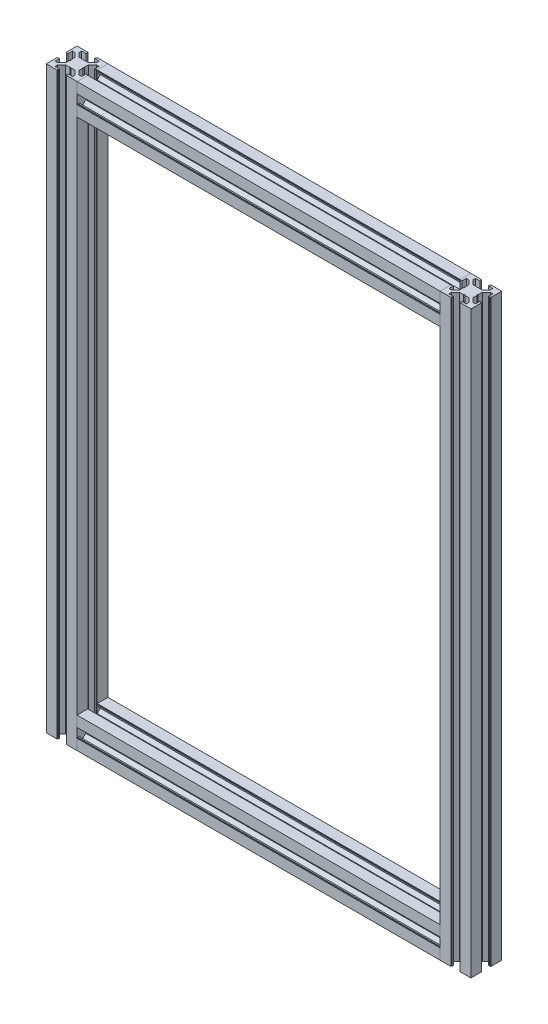
SolidWorks part; units mm, degrees
ref_plane "Ön Düzlem" through (0, 0, 0) normal (0, 0, 1) x (1, 0, 0)
ref_plane "Üst Düzlem" through (0, 0, 0) normal (0, 1, 0) x (1, 0, 0)
ref_plane "Sağ Düzlem" through (0, 0, 0) normal (1, 0, 0) x (0, 0, -1)
sketch "Sketch1" plane through (0, 0, 0) normal (0, 0, 1) x (1, 0, 0)
  line L1 (-192, 267.5) -> (192, 267.5)
  line L2 (-192, 267.5) -> (-192, -267.5)
  line L3 (-192, -267.5) -> (192, -267.5)
  line L4 (192, 267.5) -> (192, -267.5)
  line L5 (-192, 267.5) -> (192, -267.5) construction
  line L6 (-192, -267.5) -> (192, 267.5) construction
  point P0 (0, 0)
  dimension "D1" = 535
  dimension "D2" = 384
other "Square tube 30X30(1)"
ref_plane "Plane1" through (-192, 267.5, 0) normal (1, 0, 0) x (0, 1, 0)
sketch "Sketch11" plane through (-192, 267.5, 0) normal (1, 0, 0) x (0, 1, 0)
  line L0 (-14.9945, -4.5956) -> (-14.9945, -15.0055)
  line L1 (-14.9945, -15.0055) -> (-4.5847, -15.0055)
  line L2 (-4.5847, -15.0055) -> (-4.5847, -14.2046)
  line L3 (-4.5847, -14.2046) -> (-4.0945, -14.2046)
  line L4 (-4.0945, -14.2046) -> (-4.0945, -13.0055)
  line L5 (-4.0945, -13.0055) -> (-8.4945, -13.0055)
  line L6 (-8.4945, -13.0055) -> (-8.4945, -10.5542)
  line L7 (-8.4945, -10.5542) -> (-4.5847, -6.5055)
  line L8 (-4.5847, -6.5055) -> (-0.5548, -6.5055)
  line L9 (-0.5548, -6.5055) -> (0.0109, -5.9398)
  line L10 (0.0109, -5.9398) -> (0.5766, -6.5055)
  line L11 (0.5766, -6.5055) -> (4.5956, -6.5055)
  line L12 (4.5956, -6.5055) -> (8.5055, -10.5542)
  line L13 (8.5055, -10.5542) -> (8.5055, -13.0055)
  line L14 (8.5055, -13.0055) -> (4.1055, -13.0055)
  line L15 (4.1055, -13.0055) -> (4.1055, -14.2046)
  line L16 (4.1055, -14.2046) -> (4.5956, -14.2046)
  line L17 (4.5956, -14.2046) -> (4.5956, -15.0055)
  line L18 (4.5956, -15.0055) -> (15.0055, -15.0055)
  line L19 (15.0055, -15.0055) -> (15.0055, -4.5956)
  line L20 (15.0055, -4.5956) -> (14.2046, -4.5956)
  line L21 (14.2046, -4.5956) -> (14.2046, -4.1055)
  line L22 (14.2046, -4.1055) -> (13.0055, -4.1055)
  line L23 (13.0055, -4.1055) -> (13.0055, -8.5055)
  line L24 (13.0055, -8.5055) -> (10.5542, -8.5055)
  line L25 (10.5542, -8.5055) -> (6.5055, -4.5956)
  line L26 (6.5055, -4.5956) -> (6.5055, -0.5657)
  line L27 (6.5055, -0.5657) -> (5.9398, 0)
  line L28 (5.9398, 0) -> (6.5055, 0.5657)
  line L29 (6.5055, 0.5657) -> (6.5055, 4.5847)
  line L30 (6.5055, 4.5847) -> (10.5542, 8.4945)
  line L31 (10.5542, 8.4945) -> (13.0055, 8.4945)
  line L32 (13.0055, 8.4945) -> (13.0055, 4.0945)
  line L33 (13.0055, 4.0945) -> (14.2046, 4.0945)
  line L34 (14.2046, 4.0945) -> (14.2046, 4.5847)
  line L35 (14.2046, 4.5847) -> (15.0055, 4.5847)
  line L36 (15.0055, 4.5847) -> (15.0055, 14.9945)
  line L37 (15.0055, 14.9945) -> (4.5956, 14.9945)
  line L38 (4.5956, 14.9945) -> (4.5956, 14.1937)
  line L39 (4.5956, 14.1937) -> (4.1055, 14.1937)
  line L40 (4.1055, 14.1937) -> (4.1055, 12.9945)
  line L41 (4.1055, 12.9945) -> (8.5055, 12.9945)
  line L42 (8.5055, 12.9945) -> (8.5055, 10.5433)
  line L43 (8.5055, 10.5433) -> (4.5956, 6.4945)
  line L44 (4.5956, 6.4945) -> (0.5657, 6.4945)
  line L45 (0.5657, 6.4945) -> (0, 5.9289)
  line L46 (0, 5.9289) -> (-0.5657, 6.4945)
  line L47 (-0.5657, 6.4945) -> (-4.5847, 6.4945)
  line L48 (-4.5847, 6.4945) -> (-8.4945, 10.5433)
  line L49 (-8.4945, 10.5433) -> (-8.4945, 12.9945)
  line L50 (-8.4945, 12.9945) -> (-4.0945, 12.9945)
  line L51 (-4.0945, 12.9945) -> (-4.0945, 14.1937)
  line L52 (-4.0945, 14.1937) -> (-4.5847, 14.1937)
  line L53 (-4.5847, 14.1937) -> (-4.5847, 14.9945)
  line L54 (-4.5847, 14.9945) -> (-14.9945, 14.9945)
  line L55 (-14.9945, 14.9945) -> (-14.9945, 4.5847)
  line L56 (-14.9945, 4.5847) -> (-14.1937, 4.5847)
  line L57 (-14.1937, 4.5847) -> (-14.1937, 4.0945)
  line L58 (-14.1937, 4.0945) -> (-12.9945, 4.0945)
  line L59 (-12.9945, 4.0945) -> (-12.9945, 8.4945)
  line L60 (-12.9945, 8.4945) -> (-10.5433, 8.4945)
  line L61 (-10.5433, 8.4945) -> (-6.4945, 4.5847)
  line L62 (-6.4945, 4.5847) -> (-6.4945, 0.5548)
  line L63 (-6.4945, 0.5548) -> (-5.9289, -0.0109)
  line L64 (-5.9289, -0.0109) -> (-6.4945, -0.5766)
  line L65 (-6.4945, -0.5766) -> (-6.4945, -4.5956)
  line L66 (-6.4945, -4.5956) -> (-10.5433, -8.5055)
  line L67 (-10.5433, -8.5055) -> (-12.9945, -8.5055)
  line L68 (-12.9945, -8.5055) -> (-12.9945, -4.1055)
  line L69 (-12.9945, -4.1055) -> (-14.1937, -4.1055)
  line L70 (-14.1937, -4.1055) -> (-14.1937, -4.5956)
  line L71 (-14.1937, -4.5956) -> (-14.9945, -4.5956)
  point P72 (0, 0)
other "Trim/Extend1"
other "Trim/Extend2"
other "Trim/Extend3"
other "Trim/Extend5"
hole_wizard "Ø8.0 (8) Diameter Hole1" positions "Sketch12" profile "Sketch13" hole size "Ø8.0" standard "ANSI Metric" end condition through all
sketch "Sketch12" plane through (-207.0055, 0, 0) normal (-1, 0, 0) x (0, 0, 1)
  line L0 (0, 267.5) -> (0, -267.5) construction
  line L1 (0, 282.5055) -> (0, -282.5055) construction
  point P0 (0, 267.5)
  point P3 (0, -267.5)
sketch "Sketch13" plane through (-207.0055, 267.5, 0) normal (0, 1, 0) x (0, 0, 1)
  line L0 (0, 0) -> (0, 414.0109)
  line L1 (0, 414.0109) -> (4, 414.0109)
  line L2 (4, 414.0109) -> (4, 0)
  line L5 (4, 0) -> (0, 0)
  line L11 (0, -6.35) -> (0, 107.95) construction
  dimension "Thru Hole Dia." = 8
  dimension "Thru Hole Depth" = 414.0109
